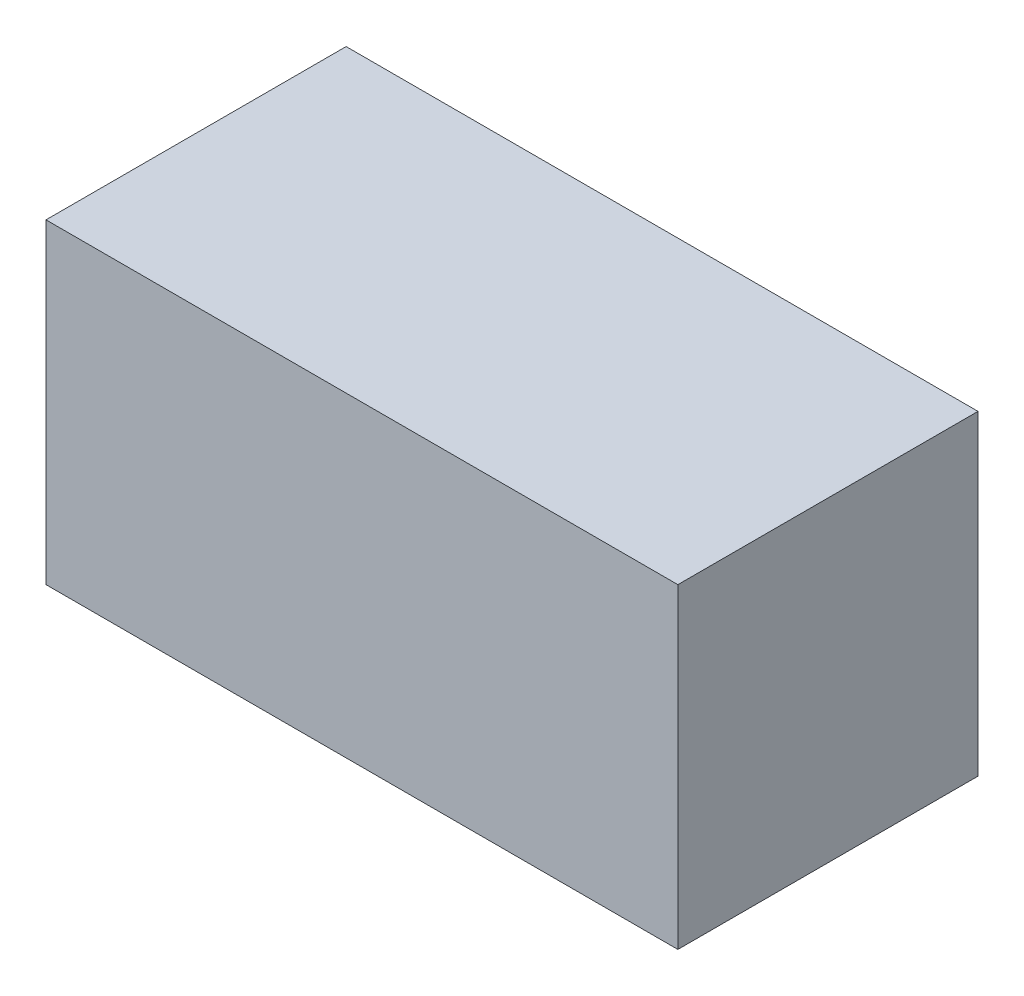
SolidWorks part; units mm, degrees
ref_plane "Front Plane" through (0, 0, 0) normal (0, 0, 1) x (1, 0, 0)
ref_plane "Top Plane" through (0, 0, 0) normal (0, 1, 0) x (1, 0, 0)
ref_plane "Right Plane" through (0, 0, 0) normal (1, 0, 0) x (0, 0, -1)
sketch "Sketch1" plane through (0, 0, 0) normal (0, 0, 1) x (1, 0, 0)
  line L1 (0, 0) -> (40, 0)
  line L2 (0, 0) -> (0, 20)
  line L3 (0, 20) -> (40, 20)
  line L4 (40, 0) -> (40, 20)
extrude "Boss-Extrude1" add sketch "Sketch1" along normal blind 19
